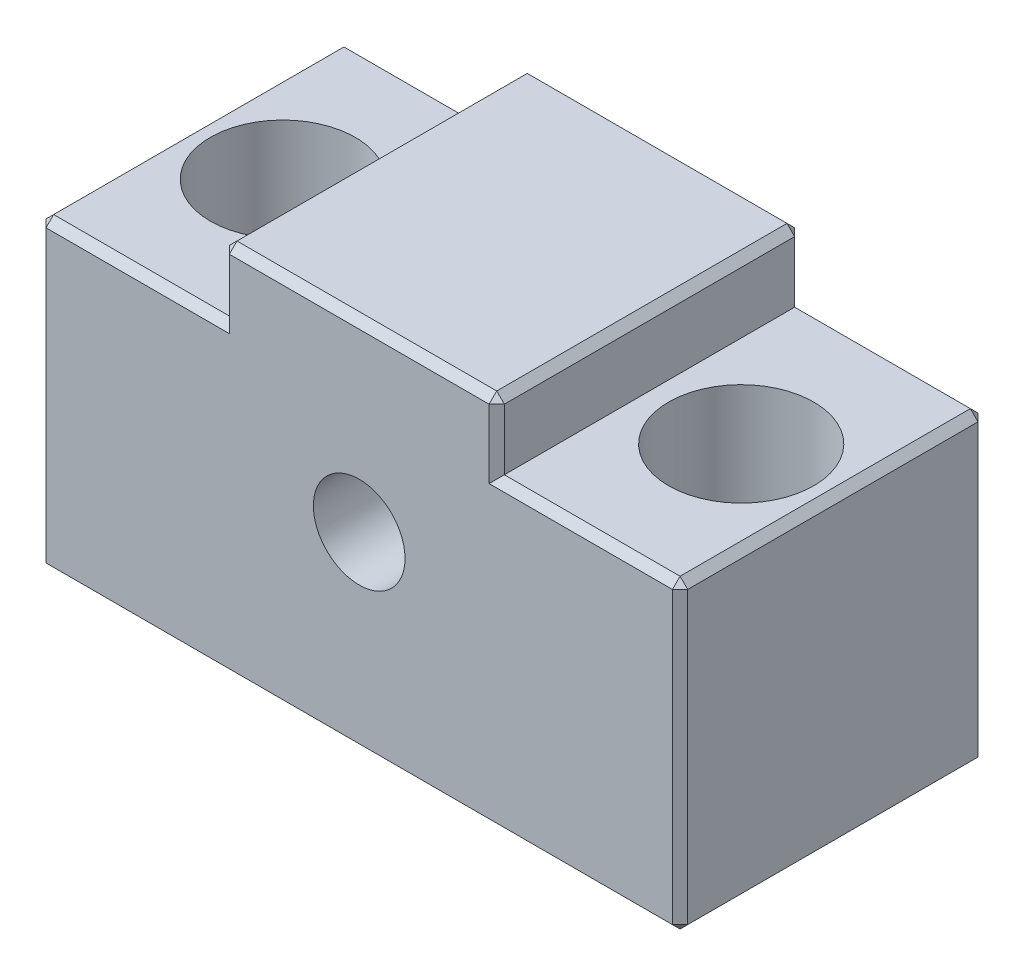
SolidWorks part; units mm, degrees
ref_plane "Front Plane" through (0, 0, 0) normal (0, 0, 1) x (1, 0, 0)
ref_plane "Top Plane" through (0, 0, 0) normal (0, 1, 0) x (1, 0, 0)
ref_plane "Right Plane" through (0, 0, 0) normal (1, 0, 0) x (0, 0, -1)
sketch "Sketch1" plane through (0, 0, 0) normal (0, 0, 1) x (1, 0, 0)
  line L0 (-21, 0) -> (21, 0)
  line L1 (21, 0) -> (21, 20)
  line L2 (21, 20) -> (9, 20)
  line L3 (9, 20) -> (9, 24.5)
  line L4 (9, 24.5) -> (-9, 24.5)
  line L5 (-9, 24.5) -> (-9, 20)
  line L6 (-9, 20) -> (-21, 20)
  line L7 (-21, 20) -> (-21, 0)
  point P4 (0, 0)
  point P11 (0, 24.5)
  dimension "D1" = 42
  dimension "D2" = 20
  dimension "D3" = 18
  dimension "D4" = 4.5
extrude "Boss-Extrude1" add sketch "Sketch1" against normal blind 20
ref_plane "Plane1" through (0, 20, 0) normal (0, 1, 0) x (1, 0, 0)
sketch "Sketch2" plane through (0, 20, 0) normal (0, 1, 0) x (1, 0, 0)
  line L0 (-9, 20) -> (-21, 20) construction
  circle A0 centre (-15, 10) radius 4.75
  point P4 (-15, 20)
  dimension "D1" = 9.5
sketch "Sketch4" plane through (0, 0, 0) normal (0, 1, 0) x (1, 0, 0)
  circle A0 centre (-15, 10) radius 2.75
  dimension "D1" = 5.5
extrude "Cut-Extrude2" cut sketch "Sketch4" along normal up to next
extrude "Cut-Extrude3" cut sketch "Sketch2" against normal blind 11.2
mirror "Mirror1" about plane through (0, 0, 0) normal (1, 0, 0) of "Cut-Extrude2", "Cut-Extrude3"
sketch "Sketch5" plane through (0, 0, 0) normal (0, 0, 1) x (1, 0, 0)
  line L0 (9, 24.5) -> (-9, 24.5) construction
  circle A0 centre (0, 12.5) radius 3
  dimension "D1" = 12
  dimension "D2" = 6
extrude "Cut-Extrude4" cut sketch "Sketch5" against normal up to next
sketch "Sketch6" plane through (0, 0, -20) normal (0, 0, -1) x (-1, 0, 0)
  circle A0 centre (0, 12.5) radius 5.5
  dimension "D1" = 11
extrude "Cut-Extrude5" cut sketch "Sketch6" against normal blind 3.5
chamfer "Chamfer1" distance 0.5 angle 45 22 edges at (-9, 24.5, -10) (0, 24.5, -20) (9, 24.5, -10) (0, 24.5, 0) (0, 0, -20) (21, 0, -10) (-21, 0, -10) (-21, 10, -20) (-9, 22.25, -20) (-15, 20, -20) (-21, 20, -10) (-9, 22.25, 0) (-15, 20, 0) (-21, 10, 0) (0, 0, 0) (9, 22.25, -20) (9, 22.25, 0) (15, 20, 0) (21, 10, 0) (21, 10, -20) (21, 20, -10) (15, 20, -20)
